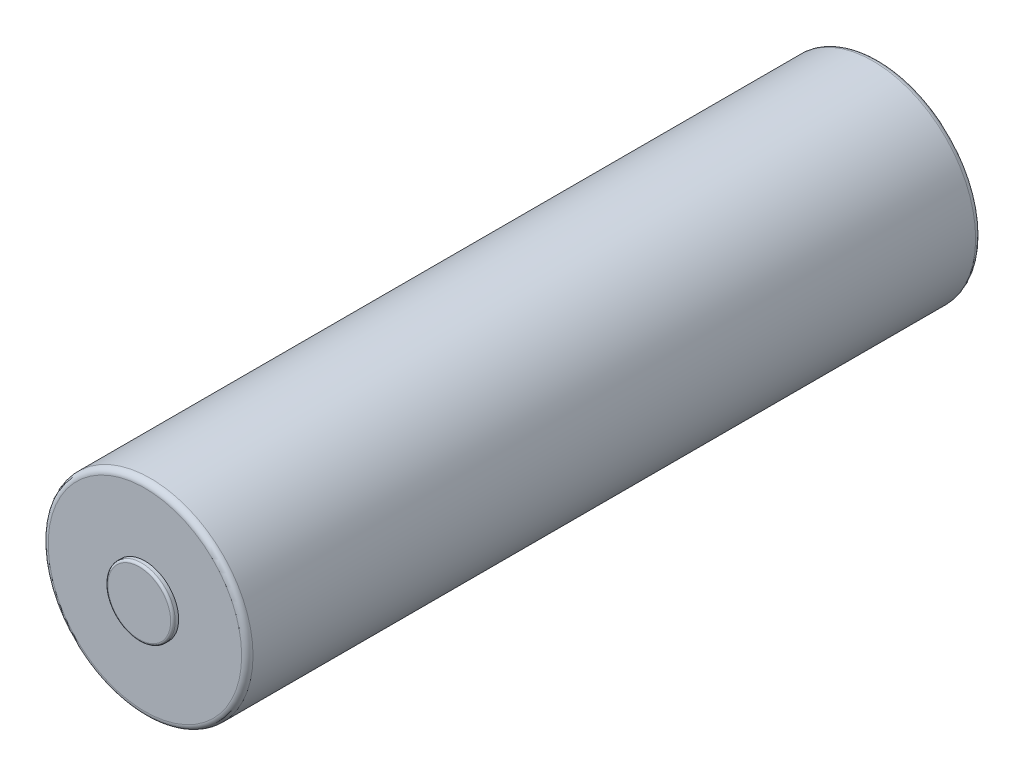
SolidWorks part; units mm, degrees
ref_plane "Front Plane" through (0, 0, 0) normal (0, 0, 1) x (1, 0, 0)
ref_plane "Top Plane" through (0, 0, 0) normal (0, 1, 0) x (1, 0, 0)
ref_plane "Right Plane" through (0, 0, 0) normal (1, 0, 0) x (0, 0, -1)
sketch "Sketch1" plane through (0, 0, 0) normal (0, 0, 1) x (1, 0, 0)
  circle A0 centre (0, 0) radius 9
  dimension "D1" = 18
extrude "Boss-Extrude1" add sketch "Sketch1" along normal blind 64.5
fillet "Fillet1" radius 0.5 2 edges at (9, 0, 0) (9, 0, 64.5)
sketch "Sketch2" plane through (0, 0, 64.5) normal (0, 0, 1) x (1, 0, 0)
  circle A0 centre (0, 0) radius 2.9622
extrude "Boss-Extrude2" add sketch "Sketch2" along normal blind 0.5
fillet "Fillet2" radius 0.2 1 edges at (2.9622, 0, 65)
